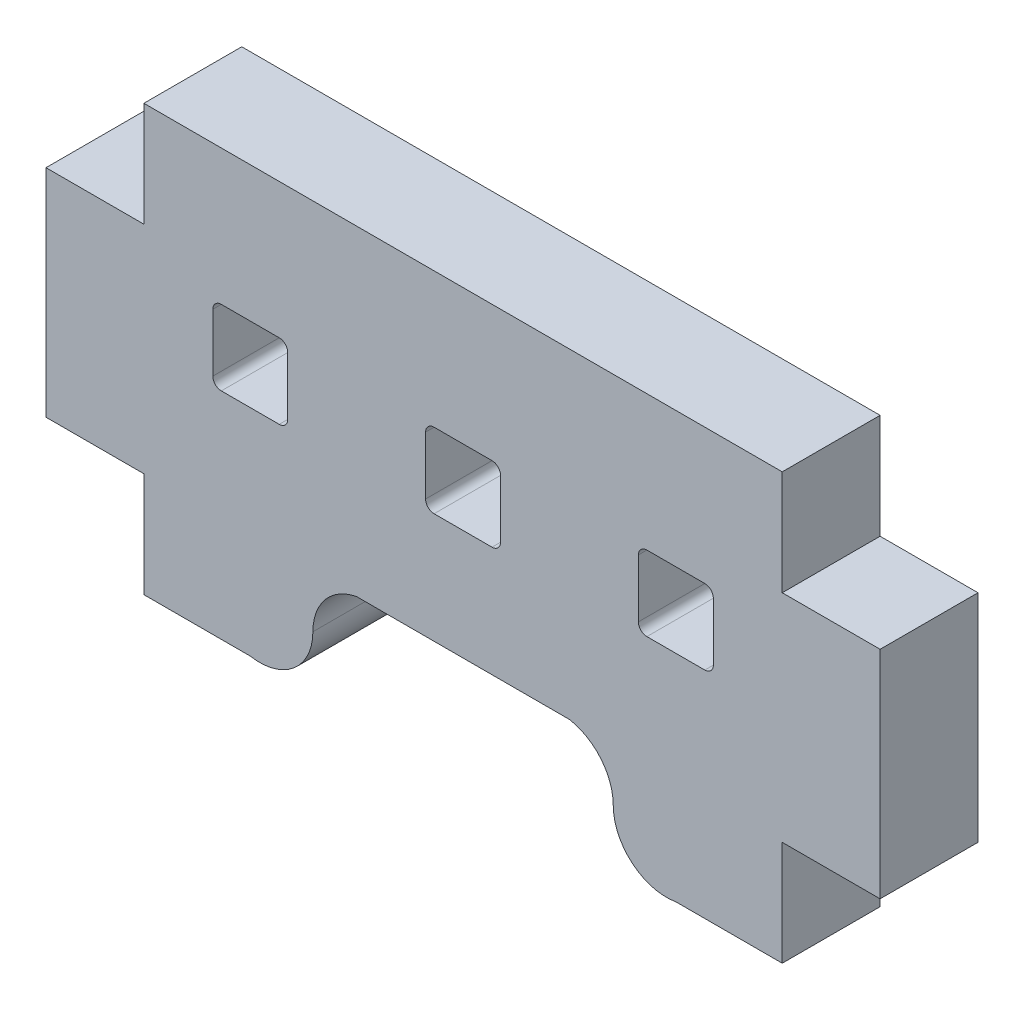
SolidWorks part; units mm, degrees
ref_plane "Front Plane" through (0, 0, 0) normal (0, 0, 1) x (1, 0, 0)
ref_plane "Top Plane" through (0, 0, 0) normal (0, 1, 0) x (1, 0, 0)
ref_plane "Right Plane" through (0, 0, 0) normal (1, 0, 0) x (0, 0, -1)
sketch "Sketch1" plane through (0, 0, 0) normal (0, 0, 1) x (1, 0, 0)
  line L0 (-19.05, 25.4) -> (-19.05, 0) construction
  line L1 (0, 0) -> (-6.35, 0)
  line L2 (0, 0) -> (0, 6.25)
  line L3 (0, 25.4) -> (-38.1, 25.4)
  line L4 (-38.1, 0) -> (-38.1, 6.25)
  line L5 (-38.1, 19.15) -> (-38.1, 25.4)
  line L6 (-38.1, 19.15) -> (-43.942, 19.15)
  line L7 (0, 19.15) -> (5.842, 19.15)
  line L8 (-38.1, 6.25) -> (-43.942, 6.25)
  line L9 (-43.942, 19.15) -> (-43.942, 6.25)
  line L10 (0, 6.25) -> (5.842, 6.25)
  line L11 (5.842, 19.15) -> (5.842, 6.25)
  line L12 (0, 19.15) -> (0, 25.4)
  line L13 (-4.6214, 16.8098) -> (-8.0786, 16.8098) construction
  line L14 (-4.6214, 12.8447) -> (-8.0786, 12.8447)
  line L15 (-4.1134, 13.3527) -> (-4.1134, 16.8098)
  line L16 (-4.6214, 17.3178) -> (-8.0786, 17.3178)
  line L17 (-8.5866, 13.3527) -> (-8.5866, 16.8098)
  line L18 (-8.0786, 13.3527) -> (-8.0786, 16.8098) construction
  line L19 (-4.6214, 13.3527) -> (-8.0786, 13.3527) construction
  line L20 (-4.6214, 13.3527) -> (-4.6214, 16.8098) construction
  line L21 (-10.2576, 15.0812) -> (-5.7844, 15.0812) construction
  line L22 (-6.35, 23.2234) -> (-6.35, 18.7502) construction
  line L23 (-16.8134, 13.3527) -> (-16.8134, 16.8098)
  line L24 (-4.1134, 17.3178) -> (-8.5866, 17.3178) construction
  line L25 (-4.1134, 12.8447) -> (-4.1134, 17.3178) construction
  line L26 (-8.5866, 12.8447) -> (-8.5866, 17.3178) construction
  line L27 (-4.1134, 12.8447) -> (-8.5866, 12.8447) construction
  line L28 (-17.3214, 17.3178) -> (-20.7786, 17.3178)
  line L29 (-21.2866, 13.3527) -> (-21.2866, 16.8098)
  line L30 (-17.3214, 12.8447) -> (-20.7786, 12.8447)
  line L31 (-29.5134, 13.3527) -> (-29.5134, 16.8098)
  line L32 (-30.0214, 17.3178) -> (-33.4786, 17.3178)
  line L33 (-33.9866, 13.3527) -> (-33.9866, 16.8098)
  line L34 (-30.0214, 12.8447) -> (-33.4786, 12.8447)
  line L35 (-12.7, 6.25) -> (-25.4, 6.25)
  line L36 (-38.1, 3.125) -> (0, 3.125) construction
  line L37 (-31.75, 0) -> (-38.1, 0)
  arc A0 (-4.6214, 17.3178) -> (-4.1134, 16.8098) centre (-4.6214, 16.8098) cw
  arc A1 (-8.0786, 17.3178) -> (-8.5866, 16.8098) centre (-8.0786, 16.8098) ccw
  arc A2 (-4.6214, 12.8447) -> (-4.1134, 13.3527) centre (-4.6214, 13.3527) ccw
  arc A3 (-8.0786, 12.8447) -> (-8.5866, 13.3527) centre (-8.0786, 13.3527) cw
  arc A4 (-17.3214, 12.8447) -> (-16.8134, 13.3527) centre (-17.3214, 13.3527) ccw
  arc A5 (-17.3214, 17.3178) -> (-16.8134, 16.8098) centre (-17.3214, 16.8098) cw
  arc A6 (-20.7786, 17.3178) -> (-21.2866, 16.8098) centre (-20.7786, 16.8098) ccw
  arc A7 (-20.7786, 12.8447) -> (-21.2866, 13.3527) centre (-20.7786, 13.3527) cw
  arc A8 (-30.0214, 12.8447) -> (-29.5134, 13.3527) centre (-30.0214, 13.3527) ccw
  arc A9 (-30.0214, 17.3178) -> (-29.5134, 16.8098) centre (-30.0214, 16.8098) cw
  arc A10 (-33.4786, 17.3178) -> (-33.9866, 16.8098) centre (-33.4786, 16.8098) ccw
  arc A11 (-33.4786, 12.8447) -> (-33.9866, 13.3527) centre (-33.4786, 13.3527) cw
  arc A12 (-25.4, 6.25) -> (-28.0138, 3.125) centre (-24.8388, 3.125) ccw
  arc A13 (-31.75, 0) -> (-28.0138, 3.125) centre (-31.1888, 3.125) ccw
  arc A14 (-12.7, 6.25) -> (-10.0862, 3.125) centre (-13.2612, 3.125) cw
  arc A15 (-6.35, 0) -> (-10.0862, 3.125) centre (-6.9112, 3.125) cw
  point P62 (-19.05, 6.25)
  dimension "D7" = 0.508
  dimension "D8" = 3
  dimension "D14" = 6.35
  dimension "D15" = 3.175
  dimension "D1" = 12.9
  dimension "D2" = 25.4
  dimension "D3" = 38.1
  dimension "D4" = 4.4732
  dimension "D5" = 4.4732
  dimension "D9" = 6.35
  dimension "D10" = 15.0812
  dimension "D11" = 5.842
  dimension "D12" = 6.25
  dimension "D13" = 12.7
  dimension "D6" = 0.508
extrude "Boss-Extrude1" add sketch "Sketch1" along normal blind 5.842
